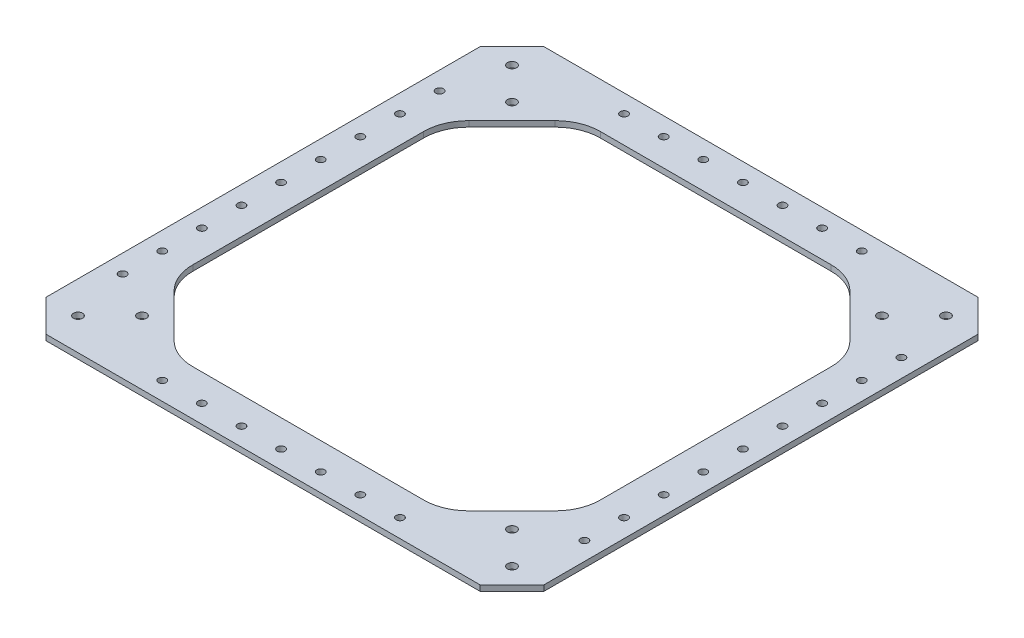
SolidWorks part; units mm, degrees
ref_plane "Front Plane" through (0, 0, 0) normal (0, 0, 1) x (1, 0, 0)
ref_plane "Top Plane" through (0, 0, 0) normal (0, 1, 0) x (1, 0, 0)
ref_plane "Right Plane" through (0, 0, 0) normal (1, 0, 0) x (0, 0, -1)
sketch "Sketch1" plane through (0, 0, 0) normal (0, 1, 0) x (1, 0, 0)
  line L0 (-139.7, 73.5201) -> (-121.7395, 91.4807)
  line L1 (-121.7395, 91.4807) -> (121.7395, 91.4807)
  line L2 (-139.7, 73.5201) -> (-139.7, -169.9588)
  line L3 (139.7, 73.5201) -> (139.7, -169.9588)
  line L4 (139.7, 73.5201) -> (121.7395, 91.4807)
  line L5 (0, 91.4807) -> (0, -187.9193) construction
  line L6 (-139.7, -48.2193) -> (139.7, -48.2193) construction
  line L7 (139.7, -169.9588) -> (121.7395, -187.9193)
  line L8 (-121.7395, -187.9193) -> (121.7395, -187.9193)
  line L9 (-139.7, -169.9588) -> (-121.7395, -187.9193)
  line L10 (-247.4631, 199.2437) -> (247.4631, 199.2437) construction
  line L11 (247.4631, 199.2437) -> (247.4631, -295.6824) construction
  line L12 (247.4631, -295.6824) -> (-247.4631, -295.6824) construction
  line L13 (-247.4631, -295.6824) -> (-247.4631, 199.2437) construction
  line L14 (-247.4631, 199.2437) -> (247.4631, -295.6824) construction
  line L15 (-247.4631, -295.6824) -> (247.4631, 199.2437) construction
  line L16 (-247.4631, 199.2437) -> (-130.7197, 82.5004) construction
  point P11 (0, -48.2193)
  point P20 (0, -48.2193)
  point P21 (-130.7197, 82.5004)
  dimension "D1" = 279.4
  dimension "D2" = 279.4
  dimension "D3" = 25.4
  dimension "D4" = 165.1
extrude "Boss-Extrude1" add sketch "Sketch1" along normal blind 3.175
sketch "Sketch2" plane through (0, 3.175, 0) normal (0, 1, 0) x (1, 0, 0)
  line L0 (-139.7, -48.2193) -> (139.7, -48.2193) construction
  line L1 (-139.7, 73.5201) -> (-139.7, -169.9588) construction
  line L2 (-103.779, 37.5991) -> (-114.3, 27.0781)
  line L3 (0, 91.4807) -> (0, -187.9193) construction
  line L4 (-85.8185, 55.5596) -> (-75.2974, 66.0807)
  line L5 (-130.7197, 82.5004) -> (-94.7987, 46.5794) construction
  line L6 (121.7395, 91.4807) -> (-121.7395, 91.4807) construction
  line L7 (-121.7395, -187.9193) -> (121.7395, -187.9193) construction
  line L8 (139.7, -169.9588) -> (139.7, 73.5201) construction
  line L9 (-114.3, 27.0781) -> (-114.3, -123.5168)
  line L10 (-121.7395, 91.4807) -> (-139.7, 73.5201) construction
  line L11 (-75.2974, 66.0807) -> (75.2974, 66.0807)
  line L12 (114.3, 27.0781) -> (114.3, -123.5168)
  line L13 (85.8185, 55.5596) -> (103.779, 37.5991)
  line L14 (85.8185, 55.5596) -> (75.2974, 66.0807)
  line L15 (103.779, 37.5991) -> (114.3, 27.0781)
  line L16 (-85.8185, -151.9983) -> (-103.779, -134.0378)
  line L17 (103.779, -134.0378) -> (114.3, -123.5168)
  line L18 (85.8185, -151.9983) -> (75.2974, -162.5193)
  line L19 (85.8185, -151.9983) -> (103.779, -134.0378)
  line L20 (-75.2974, -162.5193) -> (75.2974, -162.5193)
  line L21 (-85.8185, -151.9983) -> (-75.2974, -162.5193)
  line L22 (-103.779, -134.0378) -> (-114.3, -123.5168)
  line L23 (-85.8185, 55.5596) -> (-103.779, 37.5991)
  point P22 (114.3, -48.2193)
  point P26 (-114.3, -48.2193)
  dimension "D3" = 25.4
  dimension "D4" = 25.4
  dimension "D1" = 50.8
  dimension "D2" = 25.4
extrude "Cut-Extrude4" cut sketch "Sketch2" against normal through all
sketch "Sketch5" plane through (0, 3.175, 0) normal (0, 1, 0) x (1, 0, 0)
  line L0 (0, 91.4807) -> (0, -187.9193) construction
  line L1 (121.7395, 91.4807) -> (-121.7395, 91.4807) construction
  line L2 (139.7, -48.2193) -> (-139.7, -48.2193) construction
  line L3 (139.7, -169.9588) -> (139.7, 73.5201) construction
  line L4 (-121.7395, -187.9193) -> (121.7395, -187.9193) construction
  line L5 (-139.7, 73.5201) -> (-139.7, -169.9588) construction
  line L6 (-247.4631, 199.2437) -> (247.4631, 199.2437) construction
  line L7 (247.4631, 199.2437) -> (247.4631, -295.6824) construction
  line L8 (247.4631, -295.6824) -> (-247.4631, -295.6824) construction
  line L9 (-247.4631, -295.6824) -> (-247.4631, 199.2437) construction
  line L10 (139.7, -48.2193) -> (358.8347, -48.2193) construction
  line L11 (0, 91.4807) -> (0, 307.0068) construction
  line L12 (-247.4631, 199.2437) -> (247.4631, -295.6824) construction
  line L13 (247.4631, 199.2437) -> (-247.4631, -295.6824) construction
  line L14 (-121.7395, 91.4807) -> (-139.7, 73.5201) construction
  line L15 (-247.4631, 199.2437) -> (-94.7987, 46.5794) construction
  line L16 (-75.2974, 66.0807) -> (-114.3, 27.0781) construction
  circle A0 centre (-121.7395, 73.5201) radius 2.54
  circle A1 centre (-103.779, 55.5596) radius 2.54
  circle A2 centre (103.779, 55.5596) radius 2.54
  circle A3 centre (121.7395, 73.5201) radius 2.54
  circle A4 centre (121.7395, -169.9588) radius 2.54
  circle A5 centre (103.779, -151.9983) radius 2.54
  circle A6 centre (-103.779, -151.9983) radius 2.54
  circle A7 centre (-121.7395, -169.9588) radius 2.54
  point P9 (247.4631, -48.2193)
  point P19 (0, 199.2437)
  dimension "D2" = 5.08
  dimension "D3" = 5.08
  dimension "D1" = 165.1
  dimension "D4" = 25.4
  dimension "D5" = 12.7
extrude "Cut-Extrude3" cut sketch "Sketch5" against normal through all
sketch "Sketch4" plane through (0, 3.175, 0) normal (0, 1, 0) x (1, 0, 0)
  line L0 (-139.7, -48.2193) -> (171.6111, -48.2193) construction
  line L1 (-139.7, 73.5201) -> (-139.7, -169.9588) construction
  line L2 (121.7395, 91.4807) -> (-121.7395, 91.4807) construction
  line L3 (0, -48.2193) -> (0, -217.7016) construction
  line L4 (139.7, -169.9588) -> (139.7, 73.5201) construction
  line L5 (0, -48.2193) -> (0, 293.0757) construction
  circle A0 centre (0, 81.3207) radius 2.159
  circle A1 centre (-44.45, 81.3207) radius 2.159
  circle A2 centre (44.45, 81.3207) radius 2.159
  circle A3 centre (-22.225, 81.3207) radius 2.159
  circle A4 centre (22.225, 81.3207) radius 2.159
  circle A5 centre (-129.54, -48.2193) radius 2.159
  circle A6 centre (-129.54, -25.9943) radius 2.159
  circle A7 centre (-129.54, -3.7693) radius 2.159
  circle A8 centre (129.54, -48.2193) radius 2.159
  circle A9 centre (129.54, -25.9943) radius 2.159
  circle A10 centre (129.54, -3.7693) radius 2.159
  circle A11 centre (129.54, -92.6693) radius 2.159
  circle A12 centre (129.54, -70.4443) radius 2.159
  circle A13 centre (-129.54, -92.6693) radius 2.159
  circle A14 centre (-129.54, -70.4443) radius 2.159
  circle A15 centre (22.225, -177.7593) radius 2.159
  circle A16 centre (-22.225, -177.7593) radius 2.159
  circle A17 centre (44.45, -177.7593) radius 2.159
  circle A18 centre (-44.45, -177.7593) radius 2.159
  circle A19 centre (0, -177.7593) radius 2.159
  circle A20 centre (-66.675, 81.3207) radius 2.159
  circle A21 centre (66.675, 81.3207) radius 2.159
  circle A22 centre (-129.54, 18.4557) radius 2.159
  circle A23 centre (129.54, 18.4557) radius 2.159
  circle A24 centre (129.54, -114.8943) radius 2.159
  circle A25 centre (66.675, -177.7593) radius 2.159
  circle A26 centre (-66.675, -177.7593) radius 2.159
  circle A27 centre (-129.54, -114.8943) radius 2.159
  circle A28 centre (-129.54, -137.1193) radius 2.159
  circle A29 centre (-129.54, 40.6807) radius 2.159
  circle A30 centre (129.54, 40.6807) radius 2.159
  circle A31 centre (129.54, -137.1193) radius 2.159
  point P48 (0, 91.4807)
  dimension "D1" = 4.318
  dimension "D2" = 4.318
  dimension "D3" = 4.318
  dimension "D4" = 4.318
  dimension "D5" = 4.318
  dimension "D6" = 4.318
  dimension "D7" = 4.318
  dimension "D8" = 4.318
  dimension "D9" = 4.318
  dimension "D10" = 4.318
  dimension "D11" = 4.318
  dimension "D23" = 4.318
  dimension "D24" = 4.318
  dimension "D27" = 4.318
  dimension "D28" = 4.318
  dimension "D31" = 4.318
  dimension "D12" = 22.225
  dimension "D13" = 22.225
  dimension "D14" = 22.225
  dimension "D15" = 22.225
  dimension "D16" = 22.225
  dimension "D17" = 22.225
  dimension "D18" = 22.225
  dimension "D19" = 22.225
  dimension "D20" = 10.16
  dimension "D21" = 10.16
  dimension "D22" = 10.16
  dimension "D25" = 22.225
  dimension "D26" = 22.225
  dimension "D29" = 22.225
  dimension "D30" = 22.225
  dimension "D32" = 22.225
extrude "Cut-Extrude2" cut sketch "Sketch4" against normal through all
fillet "Fillet1" radius 25.4 8 edges at (114.3, 1.5875, 123.5168) (75.2974, 1.5875, 162.5193) (-75.2974, 1.5875, 162.5193) (-114.3, 1.5875, 123.5168) (114.3, 1.5875, -27.0781) (75.2974, 1.5875, -66.0807) (-114.3, 1.5875, -27.0781) (-75.2974, 1.5875, -66.0807)
